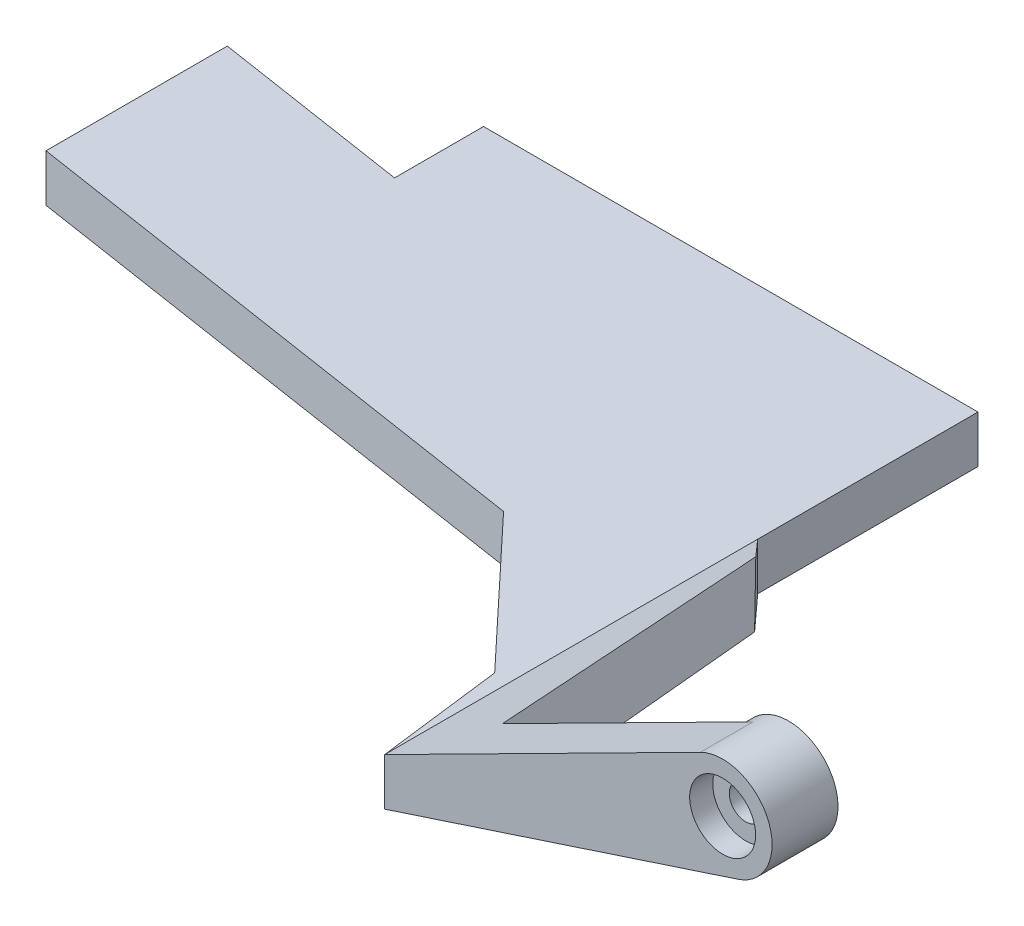
SolidWorks part; units mm, degrees
ref_plane "Alzado" through (0, 0, 0) normal (0, 0, 1) x (1, 0, 0)
ref_plane "Planta" through (0, 0, 0) normal (0, 1, 0) x (1, 0, 0)
ref_plane "Vista lateral" through (0, 0, 0) normal (1, 0, 0) x (0, 0, -1)
sketch "Croquis1" plane through (0, 0, 0) normal (0, 0, 1) x (1, 0, 0)
  circle A1 centre (10, 0) radius 2.5
  circle A2 centre (10, 0) radius 5
  circle A3 centre (10, 0) radius 6
extrude "Saliente-Extruir1" add sketch "Croquis1" along normal blind 10 contours A3 A2 | A2 A1 | A1
sketch "Croquis2" plane through (0, 0, 10) normal (0, 0, 1) x (1, 0, 0)
  circle A0 centre (10, 0) radius 2.5
  circle A1 centre (10, 0) radius 5
extrude "Saliente-Extruir2" add sketch "Croquis2" against normal blind 7
sketch "Croquis3" plane through (0, 0, 10) normal (0, 0, 1) x (1, 0, 0)
  circle A0 centre (10, 0) radius 5
  dimension "D1" = 10
extrude "Cortar-Extruir2" cut sketch "Croquis3" against normal up to vertex (3.5 mm away)
sketch "Croquis4" plane through (0, 0, 0) normal (0, 0, -1) x (-1, 0, 0)
  circle A0 centre (-10, 0) radius 6
extrude "Cortar-Extruir3" cut sketch "Croquis4" against normal up to vertex (0.8 mm away)
sketch "Croquis5" plane through (0, 0, 10) normal (0, 0, 1) x (1, 0, 0)
  circle A0 centre (10, 0) radius 7.5
  circle A1 centre (10, 0) radius 5
  dimension "D1" = 15
  dimension "D2" = 10
extrude "Saliente-Extruir3" add sketch "Croquis5" against normal up to vertex (10 mm away)
sketch "Croquis6" plane through (0, 0, 10) normal (0, 0, 1) x (1, 0, 0)
  line L0 (-41.2676, -17.5483) -> (6.6124, 6.6914)
  line L1 (-41.2676, -24.7171) -> (12.3385, -7.1261)
  line L2 (-41.2676, -17.5483) -> (-41.2676, -24.7171)
  circle A0 centre (10, 0) radius 7.5 construction
  arc A1 (6.6124, 6.6914) -> (12.3385, -7.1261) centre (10, 0) ccw
extrude "Saliente-Extruir4" add sketch "Croquis6" against normal blind 8
sketch "Croquis7" plane through (0, 0, 10) normal (0, 0, 1) x (1, 0, 0)
  line L0 (-41.2676, -24.7171) -> (-116.2676, -24.7171)
  line L1 (-41.2676, -24.7171) -> (-41.2676, -17.5483)
  line L4 (-41.2676, -17.5483) -> (-116.2676, -17.5483)
  line L5 (-116.2676, -17.5483) -> (-116.2676, -24.7171)
  dimension "D1" = 75
extrude "Saliente-Extruir5" add sketch "Croquis7" against normal blind 90 contours L5 L0 L1 L4
sketch "Croquis8" plane through (0, -24.7171, 0) normal (0, -1, 0) x (1, 0, 0)
  line L0 (-27.9791, 2) -> (-41.2676, -39)
  line L1 (-41.2676, 2) -> (12.3385, 2) construction
  line L2 (-41.2676, -80) -> (-41.2676, 2) construction
  line L3 (-41.2676, -39) -> (-41.2676, 2)
  line L4 (-41.2676, 2) -> (-27.9791, 2)
extrude "Saliente-Extruir6" add sketch "Croquis8" against normal up to vertex
sketch "Croquis10" plane through (0, 0, 2) normal (0, 0, -1) x (-1, 0, 0)
  line L0 (41.2676, -17.5483) -> (27.9791, -17.5483)
  line L1 (27.9791, -17.5483) -> (27.9791, -10.8209)
  line L2 (-6.6124, 6.6914) -> (41.2676, -17.5483) construction
  line L3 (27.9791, -10.8209) -> (41.2676, -17.5483)
extrude "Saliente-Extruir9" add sketch "Croquis10" along normal up to vertex (41 mm away)
sketch "Croquis11" plane through (0, 0, -39) normal (0, 0, -1) x (-1, 0, 0)
  line L0 (41.2676, -17.5483) -> (41.2676, -24.7171)
  line L1 (41.2676, -24.7171) -> (27.9791, -20.3564)
  line L2 (27.9791, -20.3564) -> (27.9791, -17.5483)
  line L3 (27.9791, -17.5483) -> (41.2676, -17.5483)
extrude "Saliente-Extruir10" add sketch "Croquis11" against normal up to vertex (49 mm away)
sketch "Croquis12" plane through (0, 0, 2) normal (0, 0, 1) x (1, 0, 0)
  line L0 (-41.2676, -24.7171) -> (-27.9791, -20.3564)
  line L1 (-27.9791, -20.3564) -> (-27.9791, -24.7171)
  line L2 (-27.9791, -24.7171) -> (-41.2676, -24.7171)
extrude "Cortar-Extruir4" cut sketch "Croquis12" against normal up to vertex
sketch "Croquis13" plane through (-1.3475, 2.6616, 0) normal (-0.4517, 0.8922, 0) x (0.8922, 0.4517, 0)
  line L0 (-29.8501, -2) -> (-37.2972, 39)
  line L1 (-44.7444, 39) -> (-29.8501, 39) construction
  line L2 (-37.2972, 39) -> (-29.8501, 39)
  line L3 (-29.8501, 39) -> (-29.8501, -2)
extrude "Cortar-Extruir5" cut sketch "Croquis13" against normal through all
sketch "Croquis14" plane through (3.3106, -10.0886, 0) normal (0.3118, -0.9501, 0) x (0.9501, 0.3118, 0)
  line L0 (-29.9583, 2) -> (-32.9314, 2)
  line L1 (-32.9314, 2) -> (-36.108, -39)
  line L2 (-36.108, -39) -> (-29.9583, 2)
extrude "Cortar-Extruir7" cut sketch "Croquis14" against normal through all contours L2 L0 L1
sketch "Croquis15" plane through (3.3106, -10.0886, 0) normal (0.3118, -0.9501, 0) x (0.9501, 0.3118, 0)
  line L0 (-26.1664, 2) -> (-33.7454, 2)
  line L1 (-32.9314, 2) -> (9.5015, 2) construction
  line L2 (-33.7454, 2) -> (-39.4297, -39)
  line L3 (-36.108, -39) -> (-46.917, -39) construction
  line L4 (-39.4297, -39) -> (-33.7454, -39)
  line L5 (-33.7454, -39) -> (-26.1664, 2)
extrude "Cortar-Extruir8" cut sketch "Croquis15" against normal through all
sketch "Croquis16" plane through (0, -17.5483, 0) normal (0, 1, 0) x (1, 0, 0)
  line L0 (-41.2676, -10) -> (-46.0414, 28.1515)
  line L1 (-46.0414, 28.1515) -> (-116.2676, 39)
  line L2 (-116.2676, 80) -> (-116.2676, -10) construction
  line L3 (-116.2676, 39) -> (-116.2676, -10)
  line L4 (-116.2676, -10) -> (-41.2676, -10)
extrude "Cortar-Extruir9" cut sketch "Croquis16" against normal through all
sketch "Croquis17" plane through (0, -24.7171, 0) normal (0, -1, 0) x (1, 0, 0)
  line L0 (-116.2676, -39) -> (-116.2676, -59.5)
  line L2 (-116.2676, -80) -> (-116.2676, -39) construction
  line L3 (-116.2676, -59.5) -> (-146.2676, -59.5)
  line L4 (-146.2676, -59.5) -> (-146.2676, -39)
  line L5 (-146.2676, -39) -> (-116.2676, -39)
  dimension "D1" = 20.5
  dimension "D2" = 30
extrude "Saliente-Extruir12" add sketch "Croquis17" against normal up to vertex
sketch "Croquis18" plane through (0, -24.7171, 0) normal (0, -1, 0) x (1, 0, 0)
  line L0 (-146.2676, -59.5) -> (-116.2676, -59.5)
  line L1 (-116.2676, -59.5) -> (-146.2676, -64.1442)
  line L2 (-146.2676, -64.1442) -> (-146.2676, -59.5)
  line L4 (-116.2676, -39) -> (-146.2676, -43.6344)
  line L5 (-146.2676, -39) -> (-146.2676, -59.5) construction
  line L6 (-146.2676, -43.6344) -> (-146.2676, -39)
  line L7 (-146.2676, -39) -> (-116.2676, -39)
  dimension "D1" = 8.8
extrude "Cortar-Extruir10" cut sketch "Croquis18" against normal through all contours L2 L0 L1 | L7 L4 L6
sketch "Croquis19" plane through (0, -24.7171, 0) normal (0, -1, 0) x (1, 0, 0)
  line L0 (-146.2676, -59.5) -> (-116.2676, -59.5)
  line L1 (-116.2676, -59.5) -> (-146.2676, -64.1344)
  line L2 (-146.2676, -64.1344) -> (-146.2676, -59.5)
extrude "Saliente-Extruir13" add sketch "Croquis19" against normal up to vertex (7.1687 mm away)
sketch "Croquis20" plane through (0, -24.7171, 0) normal (0, -1, 0) x (1, 0, 0)
  line L0 (-146.2676, -64.1344) -> (-116.2676, -59.5)
  line L1 (-116.2676, -59.5) -> (-116.2676, -66.5)
  line L2 (-116.2676, -80) -> (-116.2676, -59.5) construction
  line L3 (-146.2676, -64.1344) -> (-146.2676, -71.1344)
  line L4 (-146.2676, -71.1344) -> (-116.2676, -66.5)
  dimension "D2" = 7
  dimension "D1" = 7
extrude "Saliente-Extruir14" add sketch "Croquis20" against normal up to vertex (7.1687 mm away)
sketch "Croquis21" plane through (0, -24.7171, 0) normal (0, -1, 0) x (1, 0, 0)
  line L0 (-43.6545, -9.0757) -> (-64.1814, -30.9537)
  line L1 (-41.2676, 10) -> (-46.0414, -28.1515) construction
  line L2 (-46.0414, -28.1515) -> (-146.2676, -43.6344) construction
  line L3 (-64.1814, -30.9537) -> (-46.0414, -28.1515)
  line L4 (-46.0414, -28.1515) -> (-43.6545, -9.0757)
  dimension "D1" = 30
extrude "Saliente-Extruir15" add sketch "Croquis21" against normal up to vertex
sketch "Croquis22" plane through (0, -24.7171, 0) normal (0, -1, 0) x (1, 0, 0)
  line L0 (-41.2676, -39) -> (-34.1535, -39)
  line L1 (-34.1535, -39) -> (-41.2676, -39) construction
  line L2 (-34.1535, -39) -> (-41.2676, -46.5823)
  line L3 (-41.2676, -80) -> (-41.2676, -39) construction
  line L4 (-41.2676, -46.5823) -> (-41.2676, -39)
extrude "Saliente-Extruir16" add sketch "Croquis22" against normal up to vertex
sketch "Croquis23" plane through (0, 0, -39) normal (0, 0, 1) x (1, 0, 0)
  line L0 (-41.2676, -17.5483) -> (-41.2676, -15.1485)
  line L1 (-41.2676, -15.1485) -> (-36.5274, -15.1485)
  line L2 (-36.5274, -15.1485) -> (-41.2676, -17.5483)
  line L3 (-41.2676, -24.7171) -> (-34.1535, -22.3826)
  line L4 (-41.2676, -24.7171) -> (12.3385, -7.1261) construction
  line L5 (-34.1535, -22.3826) -> (-41.2676, -24.7171) construction
  line L6 (-34.1535, -22.3826) -> (-34.1535, -24.7171)
  line L7 (-34.1535, -24.7171) -> (-41.2676, -24.7171)
extrude "Cortar-Extruir11" cut sketch "Croquis23" against normal through all
sketch "Croquis24" plane through (0, 0, -39) normal (0, 0, 1) x (1, 0, 0)
  line L0 (-36.5274, -15.1485) -> (-34.1535, -15.1485)
  line L1 (-34.1535, -15.1485) -> (-34.1535, -22.3826)
  line L2 (-36.5274, -15.1485) -> (-34.1535, -22.3826) construction
  line L3 (-34.1535, -15.1485) -> (-34.1535, -22.3826) construction
  line L4 (-34.1535, -22.3826) -> (-36.5274, -15.1485)
extrude "Cortar-Extruir12" cut sketch "Croquis24" against normal through all
sketch "Croquis25" plane through (-1.3475, 2.6616, 0) normal (-0.4517, 0.8922, 0) x (0.8922, 0.4517, 0)
  line L1 (-39.4313, 39) -> (-39.8408, 41.9195)
  line L2 (-39.4313, 41.5301) -> (-44.7444, 46.5823) construction
  line L3 (-39.8408, 41.9195) -> (-39.4313, 41.5301)
  line L4 (-39.4313, 41.5301) -> (-39.4313, 39)
extrude "Cortar-Extruir13" cut sketch "Croquis25" against normal through all
sketch "Croquis26" plane through (3.3106, -10.0886, 0) normal (0.3118, -0.9501, 0) x (0.9501, 0.3118, 0)
  line L0 (-39.4297, -39) -> (-39.8345, -41.9195)
  line L1 (-39.8345, -41.9195) -> (-39.4297, -40.9333)
  line L2 (-39.4297, -40.9333) -> (-39.4297, -39)
extrude "Cortar-Extruir14" cut sketch "Croquis26" against normal through all
